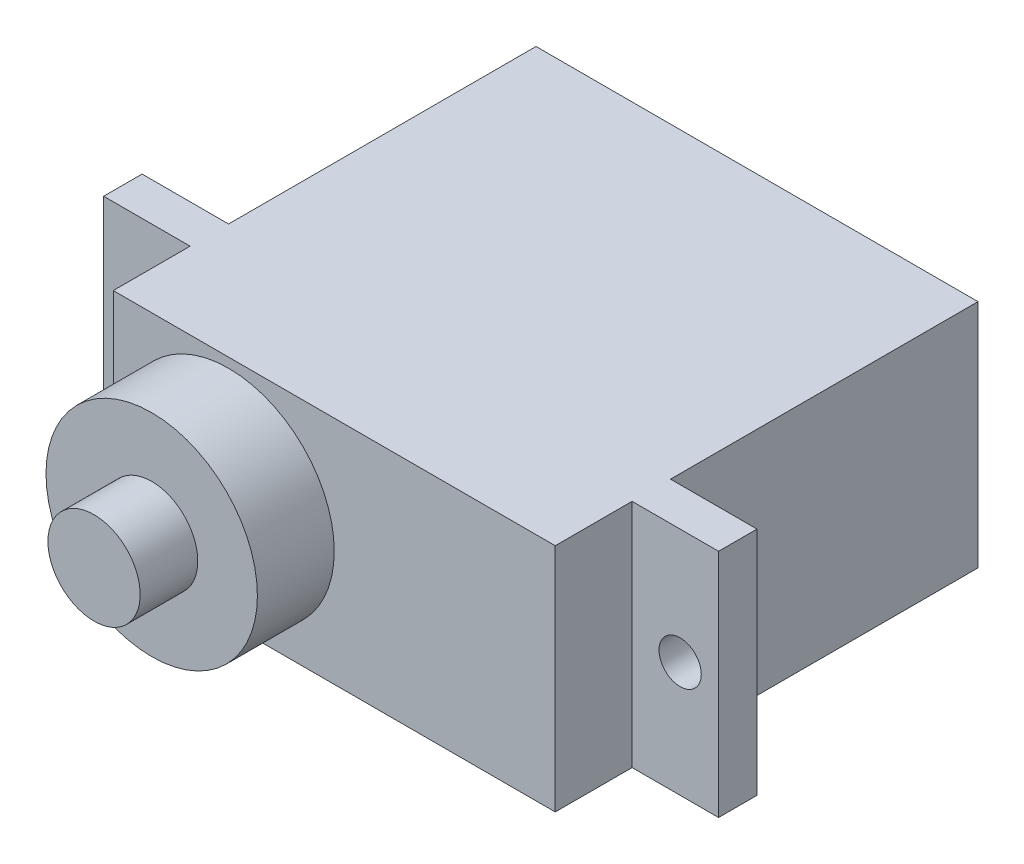
SolidWorks part; units mm, degrees
ref_plane "前视基准面" through (0, 0, 0) normal (0, 0, 1) x (1, 0, 0)
ref_plane "上视基准面" through (0, 0, 0) normal (0, 1, 0) x (1, 0, 0)
ref_plane "右视基准面" through (0, 0, 0) normal (1, 0, 0) x (0, 0, -1)
other "Configuration Table"
sketch "草图1" plane through (0, 0, 0) normal (0, 0, 1) x (1, 0, 0)
  line L1 (-11.5, -6) -> (11.5, -6)
  line L2 (-11.5, -6) -> (-11.5, 6)
  line L3 (-11.5, 6) -> (11.5, 6)
  line L4 (11.5, -6) -> (11.5, 6)
extrude "SG90_case_PHOTO_APPROX23x12x22" add sketch "草图1" along normal blind 22
sketch "草图2" plane through (0, 0, 0) normal (0, 0, 1) x (1, 0, 0)
  line L1 (-16, -6) -> (16, -6)
  line L2 (-16, -6) -> (-16, 6)
  line L3 (-16, 6) -> (16, 6)
  line L4 (16, -6) -> (16, 6)
extrude "SG90_ears_APPROX32" add sketch "草图2" along normal blind 2 from offset 16
sketch "草图3" plane through (0, 0, 0) normal (0, 0, 1) x (1, 0, 0)
  circle A0 centre (-5.5, 0) radius 5.5
extrude "SG90_top_boss_APPROX" add sketch "草图3" along normal blind 26
sketch "草图4" plane through (0, 0, 0) normal (0, 0, 1) x (1, 0, 0)
  circle A0 centre (-5.5, 0) radius 2.4
extrude "SG90_shaft_envelope_NO_SPLINE" add sketch "草图4" along normal blind 29
sketch "草图5" plane through (0, 0, 0) normal (0, 0, 1) x (1, 0, 0)
  circle A0 centre (-14, 0) radius 1.1
  circle A1 centre (14, 0) radius 1.1
extrude "SG90_ear_holes_REFERENCE28" cut sketch "草图5" against normal through all and the other way through all
